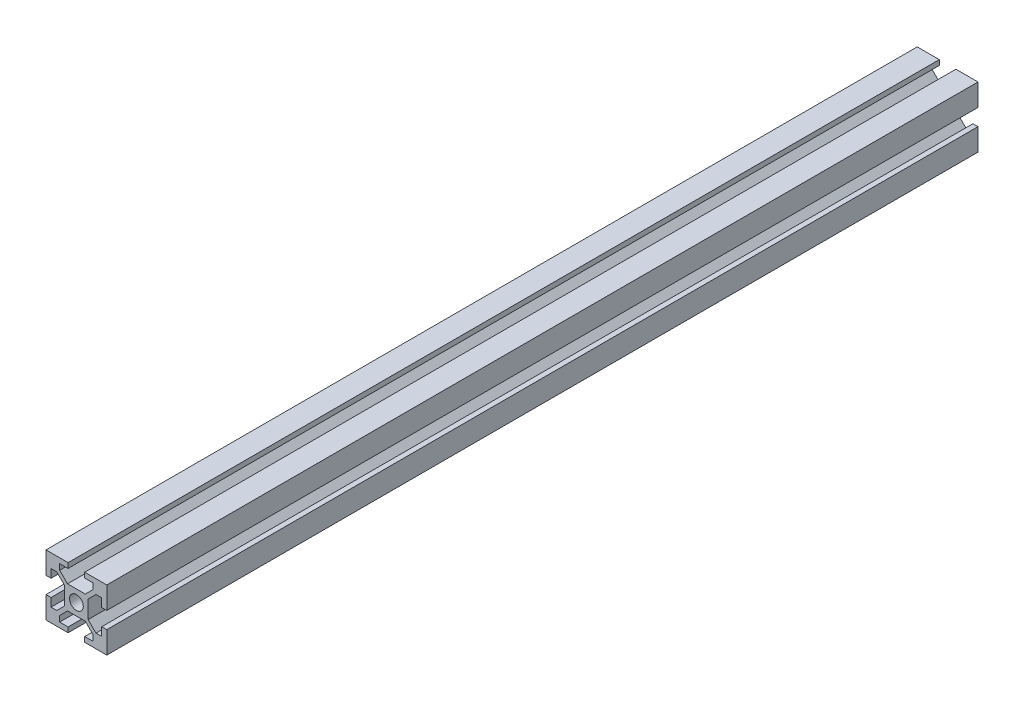
SolidWorks part; units mm, degrees
ref_plane "前视基准面" through (0, 0, 0) normal (0, 0, 1) x (1, 0, 0)
ref_plane "上视基准面" through (0, 0, 0) normal (0, 1, 0) x (1, 0, 0)
ref_plane "右视基准面" through (0, 0, 0) normal (1, 0, 0) x (0, 0, -1)
sketch "草图1" plane through (0, 0, 0) normal (0, 0, 1) x (1, 0, 0)
  line L0 (-4.1, 15) -> (-4.1, 12.5)
  line L1 (-4.3858, -5.8) -> (4.3858, -5.8)
  line L2 (-5.8, -4.3858) -> (-5.8, 4.3858)
  line L3 (-4.3858, 5.8) -> (4.3858, 5.8)
  line L4 (5.8, -4.3858) -> (5.8, 4.3858)
  line L5 (-9.6642, 8.25) -> (-12.5, 8.25)
  line L6 (-8.25, -12.5) -> (-4.1, -12.5)
  line L7 (-15, -15) -> (-4.1, -15)
  line L8 (-15, -15) -> (-15, -4.1)
  line L9 (-8.25, 15) -> (-4.1, 15)
  line L10 (15, -15) -> (15, -4.1)
  line L11 (-8.25, 9.6642) -> (-8.25, 12.5)
  line L12 (-8.25, 15) -> (-15, 15)
  line L13 (9.6642, 8.25) -> (12.5, 8.25)
  line L14 (8.25, 9.6642) -> (8.25, 12.5)
  line L15 (8.25, 15) -> (15, 15)
  line L16 (15, 8.25) -> (15, 15)
  line L17 (9.6642, -8.25) -> (12.5, -8.25)
  line L18 (8.25, -9.6642) -> (8.25, -12.5)
  line L19 (8.25, -15) -> (15, -15)
  line L20 (15, -8.25) -> (15, -15)
  line L21 (-15, 8.25) -> (-15, 15)
  line L22 (-9.6642, -8.25) -> (-12.5, -8.25)
  line L23 (-8.25, -9.6642) -> (-8.25, -12.5)
  line L24 (-8.25, -15) -> (-15, -15)
  line L25 (-15, -8.25) -> (-15, -15)
  line L26 (-12.5, -8.25) -> (-12.5, -4.1)
  line L27 (-8.25, 12.5) -> (-4.1, 12.5)
  line L28 (12.5, -8.25) -> (12.5, -4.1)
  line L29 (-8.25, 9.6642) -> (-4.3858, 5.8)
  line L30 (-9.6642, 8.25) -> (-5.8, 4.3858)
  line L31 (8.25, 9.6642) -> (4.3858, 5.8)
  line L32 (9.6642, 8.25) -> (5.8, 4.3858)
  line L33 (4.3858, -5.8) -> (8.25, -9.6642)
  line L34 (-5.8, -4.3858) -> (-9.6642, -8.25)
  line L35 (4.1, 15) -> (4.1, 12.5)
  line L36 (5.8, -4.3858) -> (9.6642, -8.25)
  line L37 (-4.3858, -5.8) -> (-8.25, -9.6642)
  line L38 (4.1, 15) -> (15, 15)
  line L39 (4.1, 12.5) -> (8.25, 12.5)
  line L40 (-4.1, -12.5) -> (-4.1, -15)
  line L41 (4.1, -15) -> (15, -15)
  line L42 (4.1, -12.5) -> (8.25, -12.5)
  line L43 (4.1, -12.5) -> (4.1, -15)
  line L44 (-15, 4.1) -> (-12.5, 4.1)
  line L45 (-15, -4.1) -> (-12.5, -4.1)
  line L46 (-15, 4.1) -> (-15, 15)
  line L47 (-12.5, 4.1) -> (-12.5, 8.25)
  line L48 (12.5, -4.1) -> (15, -4.1)
  line L49 (12.5, 4.1) -> (15, 4.1)
  line L50 (12.5, 4.1) -> (12.5, 8.25)
  line L51 (15, 4.1) -> (15, 15)
  line L52 (-15, 8.25) -> (-15, 4.1)
  line L53 (15, 8.25) -> (15, 4.1)
  line L54 (8.25, -15) -> (4.1, -15)
  line L55 (8.25, 15) -> (4.1, 15)
  circle A0 centre (0, 0) radius 3.4
extrude "凸台-拉伸1" add sketch "草图1" along normal blind 430 contours L49 L51 L16 L15 L38 L35 L39 L14 L31 L3 L29 L11 L27 L0 L9 L12 L21 L46 L44 L47 L5 L30 L2 L34 L22 L26 L45 L8 L7 L40 L6 L23 L37 L1 L33 L18 L42 L43 L41 L19 L10 L48 L28 L17 L36 L4 L32 L13
